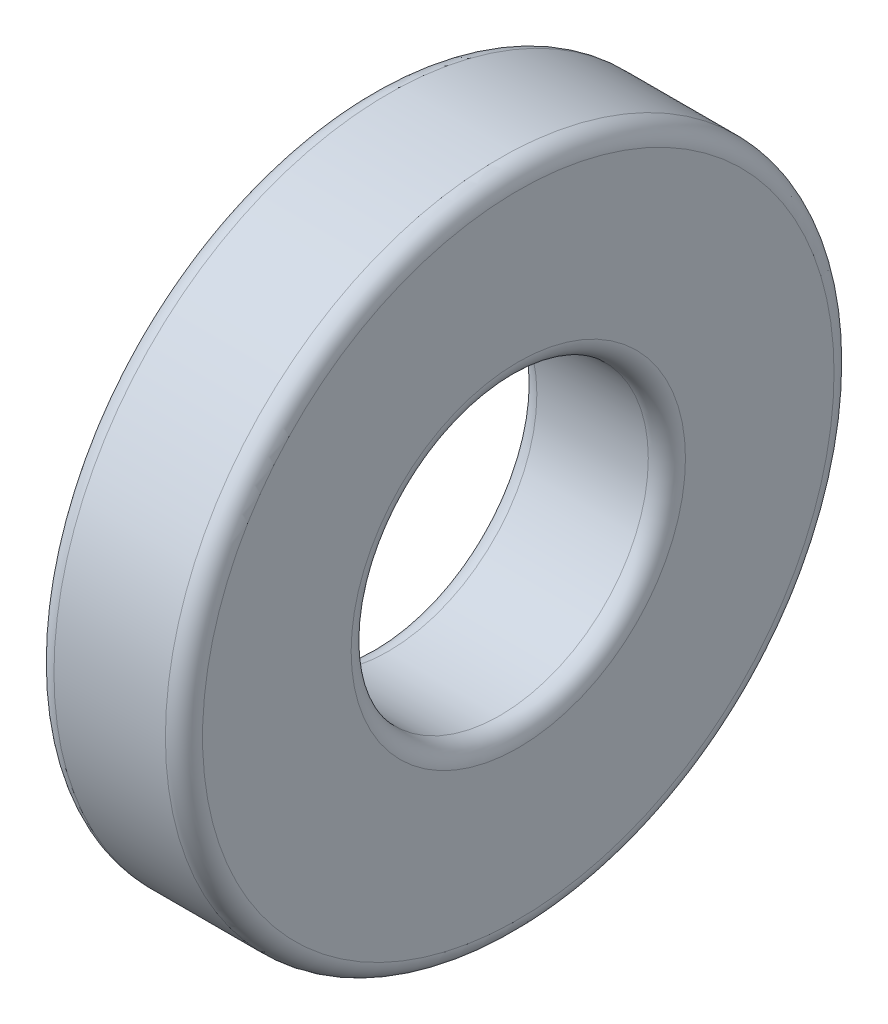
SolidWorks part; units mm, degrees
ref_plane "Front Plane" through (0, 0, 0) normal (0, 0, 1) x (1, 0, 0)
ref_plane "Top Plane" through (0, 0, 0) normal (0, 1, 0) x (1, 0, 0)
ref_plane "Right Plane" through (0, 0, 0) normal (1, 0, 0) x (0, 0, -1)
sketch "Sketch1" plane through (0, 0, 0) normal (0, 0, 1) x (1, 0, 0)
  line L0 (0, 0) -> (-67.4843, 0) construction
  line L1 (0, 0) -> (0, 6.35) construction
  line L2 (-3.175, 14.2875) -> (3.175, 14.2875)
  line L3 (-3.175, 14.2875) -> (-3.175, 6.35)
  line L4 (-3.175, 6.35) -> (3.175, 6.35)
  line L5 (3.175, 14.2875) -> (3.175, 6.35)
  dimension "D1" = 28.575
  dimension "D2" = 12.7
  dimension "D3" = 6.35
revolve "Revolve1" add sketch "Sketch1" angle 360 about L0
fillet "Fillet1" radius 0.7937 4 edges at (-3.175, 0, -6.35) (-3.175, 0, -14.2875) (3.175, 0, -6.35) (3.175, 0, -14.2875)
